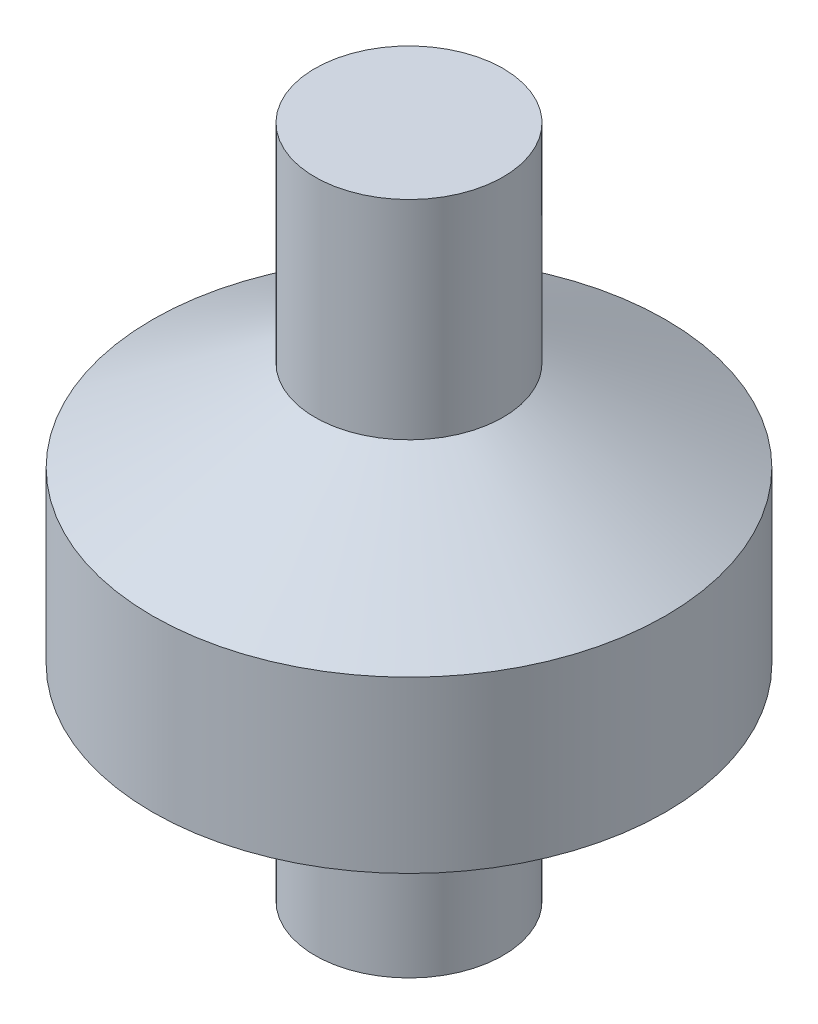
SolidWorks part; units mm, degrees
material "ABS PC"
ref_plane "Alzado" through (0, 0, 0) normal (0, 0, 1) x (1, 0, 0)
ref_plane "Planta" through (0, 0, 0) normal (0, 1, 0) x (1, 0, 0)
ref_plane "Vista lateral" through (0, 0, 0) normal (1, 0, 0) x (0, 0, -1)
sketch "Croquis1" plane through (0, 0, 0) normal (0, 0, 1) x (1, 0, 0)
  line L0 (0, 12.1665) -> (11, 12.1665)
  line L1 (11, -12.1665) -> (-11, -12.1665) construction
  line L2 (11, -12.1665) -> (11, 12.1665) construction
  line L3 (11, 12.1665) -> (-11, 12.1665) construction
  line L4 (-11, -12.1665) -> (-11, 12.1665) construction
  line L5 (11, -12.1665) -> (-11, 12.1665) construction
  line L6 (11, 12.1665) -> (-11, -12.1665) construction
  line L7 (11, 12.1665) -> (11, -12.1665)
  line L8 (11, -12.1665) -> (30, -22.7663)
  line L9 (30, -22.7663) -> (30, -42.6401)
  line L10 (30, -42.6401) -> (20.9167, -42.6401)
  line L11 (20.9167, -42.6401) -> (20.9167, -45.7507)
  line L12 (20.9167, -45.7507) -> (11, -45.7507)
  line L13 (11, -45.7507) -> (11, -66.6581)
  line L14 (11, -66.6581) -> (0, -66.6581)
  line L15 (0, -66.6581) -> (0, 12.1665)
  point P0 (0, 0)
  dimension "D1" = 22
  dimension "D2" = 30
revolve "Revolución1" add sketch "Croquis1" angle 360 about L15
